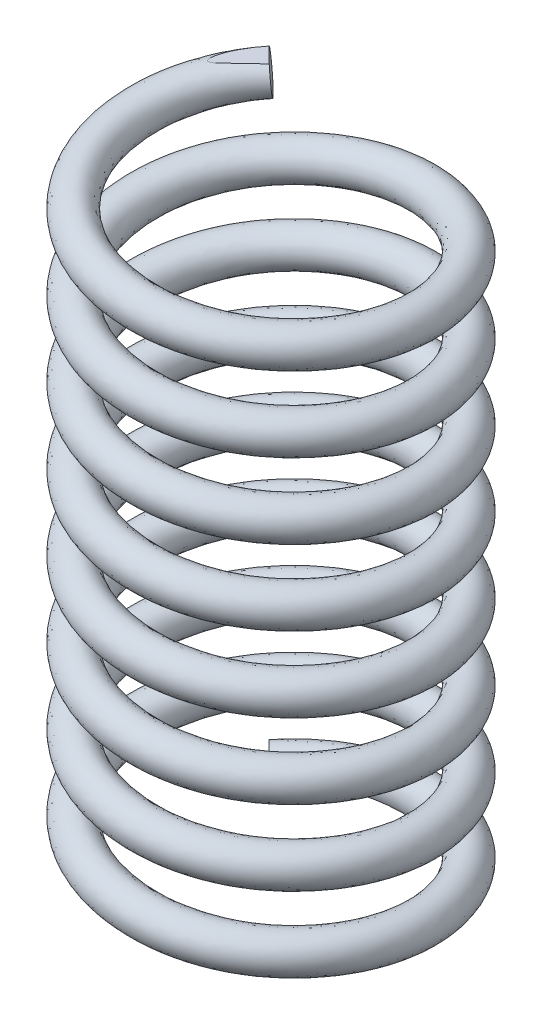
SolidWorks part; units mm, degrees
material "Chrome Stainless Steel"
ref_plane "Front Plane" through (0, 0, 0) normal (0, 0, 1) x (1, 0, 0)
ref_plane "Top Plane" through (0, 0, 0) normal (0, 1, 0) x (1, 0, 0)
ref_plane "Right Plane" through (0, 0, 0) normal (1, 0, 0) x (0, 0, -1)
sketch "Sketch1" plane through (0, 0, 0) normal (0, 1, 0) x (1, 0, 0)
  circle A0 centre (0, 0) radius 0.75
  dimension "D1" = 1.5
curve "Helix/Spiral1" pitch 0.4025 height 3.22 turns 8
sweep "Sweep1" add path "Helix/Spiral1" circular profile diameter 0.2 parameters "D3"=0.2
sketch "Sketch5" plane through (0, 0, 0) normal (1, 0, 0) x (0, 0, -1)
  line L1 (0, 0) -> (1, 0)
  line L2 (0, 0) -> (0, -0.2)
  line L3 (0, -0.2) -> (1, -0.2)
  line L4 (1, 0) -> (1, -0.2)
  line L5 (-2.0954, 3.5296) -> (0.9046, 3.5296)
  line L6 (-2.0954, 3.5296) -> (-2.0954, 3.3)
  line L7 (-2.0954, 3.3) -> (0.9046, 3.3)
  line L8 (0.9046, 3.5296) -> (0.9046, 3.3)
  dimension "D1" = 0.2
  dimension "D2" = 1
  dimension "D3" = 0.2296
  dimension "D4" = 3
  dimension "D5" = 3.3
  dimension "D6" = 0.9046
extrude "Cut-Extrude1" cut sketch "Sketch5" against normal through all both and the other way through all
